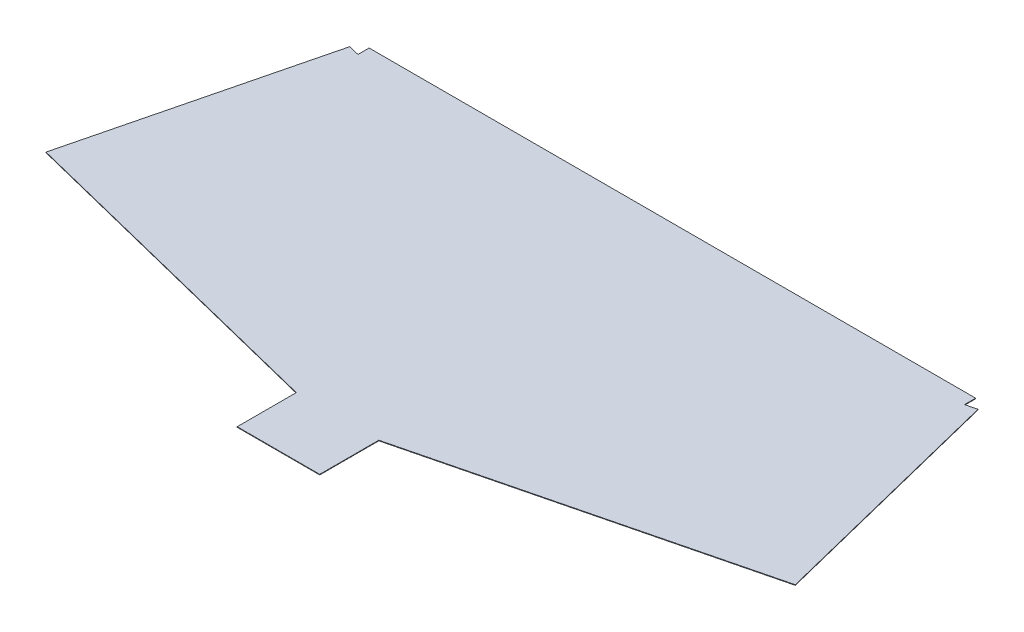
SolidWorks part; units mm, degrees
ref_plane "Front Plane" through (0, 0, 0) normal (0, 0, 1) x (1, 0, 0)
ref_plane "Top Plane" through (0, 0, 0) normal (0, 1, 0) x (1, 0, 0)
ref_plane "Right Plane" through (0, 0, 0) normal (1, 0, 0) x (0, 0, -1)
sketch "Sketch1" plane through (0, 0, 0) normal (0, 1, 0) x (1, 0, 0)
  line L0 (-432.3097, -519.7331) -> (-1010.9992, -375.4836)
  line L1 (-902.3097, 60.9164) -> (185.6903, 60.9164)
  line L2 (-902.3097, 60.9164) -> (-432.3097, -519.7331)
  line L3 (-432.3097, -519.7331) -> (-284.3097, -519.7331)
  line L4 (185.6903, 60.9164) -> (-284.3097, -519.7331)
  line L5 (-902.3097, 60.9164) -> (185.6903, 60.9164)
  line L6 (-902.3097, 60.9164) -> (-902.3097, 80.9164)
  line L7 (-902.3097, 80.9164) -> (185.6903, 80.9164)
  line L8 (185.6903, 60.9164) -> (185.6903, 80.9164)
  line L9 (-432.3097, -519.7331) -> (-284.3097, -519.7331)
  line L10 (-432.3097, -519.7331) -> (-432.3097, -625.7331)
  line L11 (-432.3097, -625.7331) -> (-284.3097, -625.7331)
  line L12 (-284.3097, -519.7331) -> (-284.3097, -625.7331)
  line L13 (-1010.9992, -375.4836) -> (-902.3097, 60.9164)
  line L14 (-284.3097, -519.7331) -> (294.3797, -375.4836)
  line L15 (294.3797, -375.4836) -> (185.6903, 60.9164)
  line L16 (-902.3097, 60.9164) -> (-1010.9992, -375.4836)
  line L17 (-902.3097, 60.9164) -> (-921.7169, 65.7499)
  line L18 (-1010.9992, -375.4836) -> (-1030.4063, -370.65)
  line L19 (-921.7169, 65.7499) -> (-1030.4063, -370.65)
  line L20 (294.3797, -375.4836) -> (185.6903, 60.9164)
  line L21 (294.3797, -375.4836) -> (313.7868, -370.65)
  line L22 (185.6903, 60.9164) -> (205.0974, 65.7499)
  line L23 (313.7868, -370.65) -> (205.0974, 65.7499)
  dimension "D1" = 1088
  dimension "D2" = 148
  dimension "D3" = 747.03
  dimension "D4" = 747.03
  dimension "D5" = 580.6495
  dimension "D6" = 20
  dimension "D7" = 106
  dimension "D8" = 596.397
  dimension "D9" = 449.7314
  dimension "D10" = 596.397
  dimension "D11" = 449.7314
  dimension "D12" = 20
  dimension "D13" = 20
extrude "Boss-Extrude1" add sketch "Sketch1" along normal blind 1 contours L14 L15 L4 | L12 L3 L10 L11 | L21 L23 L22 L15 | L1 L8 L7 L6 | L17 L19 L18 L13 | L13 L0 L2 | L4 L1 L2 L3
